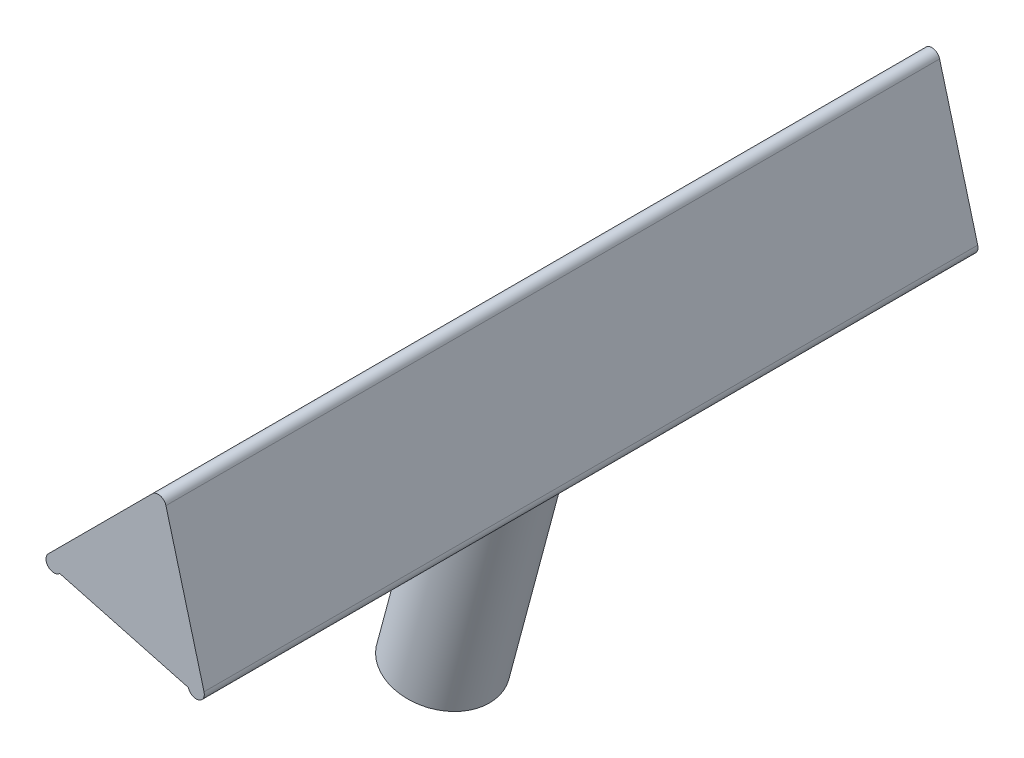
SolidWorks part; units mm, degrees
ref_plane "Front Plane" through (0, 0, 0) normal (0, 0, 1) x (1, 0, 0)
ref_plane "Top Plane" through (0, 0, 0) normal (0, 1, 0) x (1, 0, 0)
ref_plane "Right Plane" through (0, 0, 0) normal (1, 0, 0) x (0, 0, -1)
sketch "Sketch1" plane through (0, 0, 0) normal (0, 0, 1) x (1, 0, 0)
  line L0 (0, 40.7823) -> (0, -25.3365) construction
  line L1 (-57.4474, 0) -> (54.7377, 0) construction
  line L6 (0, 0) -> (6.4587, 6.4587)
  line L7 (7.2952, 6.2346) -> (9.6593, -2.5882)
  line L8 (0.7071, -0.7071) -> (5.9411, 4.5268)
  line L9 (6.7776, 4.3027) -> (8.6933, -2.847)
  line L10 (0.7071, -0.7071) -> (6.5534, 5.1392) construction
  line L11 (6.5534, 5.1392) -> (8.6933, -2.847) construction
  line L12 (0, 0) -> (7.0711, 7.0711) construction
  line L13 (7.0711, 7.0711) -> (9.6593, -2.5882) construction
  arc A2 (0, 0) -> (0.7071, -0.7071) centre (0.3536, -0.3536) ccw
  arc A3 (9.6593, -2.5882) -> (8.6933, -2.847) centre (9.1763, -2.7176) cw
  arc A4 (5.9411, 4.5268) -> (6.7776, 4.3027) centre (6.2946, 4.1733) cw
  arc A5 (6.4587, 6.4587) -> (7.2952, 6.2346) centre (6.8122, 6.1051) cw
  point P19 (7.0711, 7.0711)
  dimension "D5" = 0.5
  dimension "D1" = 45
  dimension "D2" = 60
  dimension "D3" = 10
  dimension "D4" = 1
extrude "Boss-Extrude1" add sketch "Sketch1" along normal mid plane 48
sketch "Sketch2" plane through (0, 0, 24) normal (0, 0, 1) x (1, 0, 0)
  line L0 (0.7071, -0.7071) -> (5.9411, 4.5268)
  line L1 (0.7071, -0.7071) -> (5.9411, 4.5268) construction
  line L2 (6.7776, 4.3027) -> (8.6933, -2.847)
  line L3 (6.7776, 4.3027) -> (8.6933, -2.847) construction
  line L4 (8.6933, -2.847) -> (0.7071, -0.7071)
  arc A0 (6.7776, 4.3027) -> (5.9411, 4.5268) centre (6.2946, 4.1733) ccw construction
  arc A1 (5.9411, 4.5268) -> (6.7776, 4.3027) centre (6.2946, 4.1733) cw
  arc A2 (8.6933, -2.847) -> (9.6593, -2.5882) centre (9.1763, -2.7176) ccw construction
extrude "Boss-Extrude2" add sketch "Sketch2" against normal blind 48
sketch "Sketch3" plane through (-0.1294, -0.483, 0) normal (-0.2588, -0.9659, 0) x (0.9659, -0.2588, 0)
  circle A0 centre (5, 0) radius 3
  dimension "D1" = 6
extrude "Boss-Extrude3" add sketch "Sketch3" along normal blind 16.34
